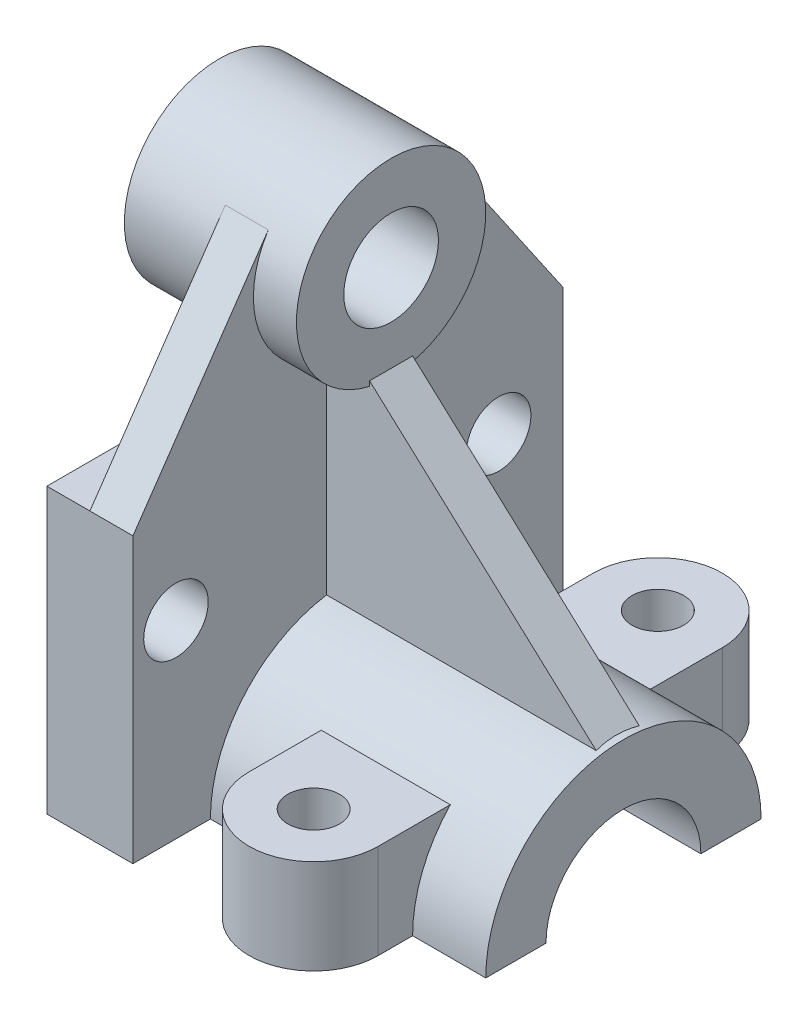
SolidWorks part; units mm, degrees
ref_plane "Front Plane" through (0, 0, 0) normal (0, 0, 1) x (1, 0, 0)
ref_plane "Top Plane" through (0, 0, 0) normal (0, 1, 0) x (1, 0, 0)
ref_plane "Right Plane" through (0, 0, 0) normal (1, 0, 0) x (0, 0, -1)
sketch "Sketch2" plane through (0, 0, 0) normal (0, 0, 1) x (1, 0, 0)
  line L0 (-22.1014, 0) -> (-22.1014, 66)
  line L1 (-22.1014, 66) -> (-2.1014, 66)
  line L2 (-2.1014, 66) -> (-2.1014, 0)
  line L3 (-2.1014, 0) -> (-22.1014, 0)
  dimension "D1" = 66
  dimension "D2" = 20
extrude "Boss-Extrude1" add sketch "Sketch2" against normal blind 100
sketch "Sketch3" plane through (-2.1014, 0, 0) normal (1, 0, 0) x (0, 0, -1)
  line L0 (0, 66) -> (100, 66)
  line L1 (0, 66) -> (32.2775, 113.0351)
  line L2 (67.7225, 113.0351) -> (100, 66)
  line L3 (100, 0) -> (0, 0) construction
  circle A0 centre (50, 100) radius 22
  circle A1 centre (50, 100) radius 11
  line M6 (100, 66) -> (0, 66)
  dimension "D1" = 44
  dimension "D2" = 22
  dimension "D3" = 100
extrude "Boss-Extrude2" add sketch "Sketch3" against normal blind 10 contours A0 L1 L2 M6 | L1 A0 L2 A1
sketch "Sketch4" plane through (-2.1014, 0, 0) normal (1, 0, 0) x (0, 0, -1)
  circle A1 centre (50, 100) radius 22
  circle A2 centre (50, 100) radius 11
extrude "Boss-Extrude3" add sketch "Sketch4" along normal blind 10
sketch "Sketch5" plane through (7.8986, 0, 0) normal (1, 0, 0) x (0, 0, -1)
  circle A0 centre (50, 100) radius 11
  circle A1 centre (50, 100) radius 22
extrude "Boss-Extrude4" add sketch "Sketch5" against normal blind 40
sketch "Sketch6" plane through (-2.1014, 0, 0) normal (1, 0, 0) x (0, 0, -1)
  line L0 (100, 0) -> (0, 0) construction
  line L1 (1.936, 0) -> (100, 0)
  circle A0 centre (50, 0) radius 32
  circle A1 centre (50, 0) radius 18
  dimension "D1" = 64
  dimension "D2" = 36
extrude "Boss-Extrude5" add sketch "Sketch6" along normal blind 64 contours A1 L1 A0
ref_plane "Plane1" through (0, 0, -50) normal (0, 0, -1) x (-1, 0, 0)
sketch "Sketch9" plane through (0, 0, -50) normal (0, 0, -1) x (-1, 0, 0)
  line L0 (-61.8986, 30.403) -> (4.3565, 30.403)
  line L1 (-61.8986, 30.403) -> (-7.8986, 79.7071)
  line L2 (-7.8986, 122) -> (-7.8986, 78) construction
  line L3 (-61.8986, 32) -> (-61.8986, 0) construction
  line L8 (-7.8986, 79.7071) -> (4.3565, 79.7071)
  line L9 (4.3565, 79.7071) -> (4.3565, 30.403)
extrude "Boss-Extrude10" add sketch "Sketch9" along normal mid plane 10
ref_plane "Plane2" through (29.8986, 0, 0) normal (1, 0, 0) x (0, 0, -1)
sketch "Sketch16" plane through (0, 0, 0) normal (0, -1, 0) x (1, 0, 0)
  line L0 (14.8986, -32) -> (14.8986, -10)
  line L1 (61.8986, -32) -> (-2.1014, -32) construction
  line L2 (44.8986, -32) -> (44.8986, -10)
  line L3 (14.8986, -68) -> (14.8986, -90)
  line L4 (61.8986, -68) -> (-2.1014, -68) construction
  line L5 (44.8986, -68) -> (44.8986, -90)
  line L6 (14.8986, -32) -> (44.8986, -32)
  line L7 (14.8986, -68) -> (44.8986, -68)
  line L8 (-2.1014, -100) -> (-2.1014, -82) construction
  arc A0 (14.8986, -10) -> (44.8986, -10) centre (29.8986, -10) cw
  arc A1 (14.8986, -90) -> (44.8986, -90) centre (29.8986, -90) ccw
  circle A2 centre (29.8986, -90) radius 6
  circle A3 centre (29.8986, -10) radius 6
  dimension "D1" = 15
  dimension "D3" = 12
  dimension "D4" = 12
  dimension "D2" = 32
  dimension "D5" = 80
extrude "Boss-Extrude11" add sketch "Sketch16" against normal blind 22
sketch "Sketch18" plane through (-2.1014, 0, 0) normal (1, 0, 0) x (0, 0, -1)
  line L0 (18, 0) -> (32, 0) construction
  line L1 (45, 79.7071) -> (45, 31.607) construction
  line L2 (100, 0) -> (100, 66) construction
  line L3 (100, 0) -> (82, 0) construction
  circle A0 centre (10, 44) radius 7.5
  circle A1 centre (85, 44) radius 7.5
  point P10 (0, 0)
  dimension "D3" = 15
  dimension "D4" = 15
  dimension "D1" = 44
  dimension "D2" = 35
  dimension "D5" = 15
  dimension "D6" = 44
extrude "Cut-Extrude2" cut sketch "Sketch18" against normal blind 22
sketch "Sketch10" plane through (0, 0, -45) normal (0, 0, 1) x (1, 0, 0)
  line L0 (7.8986, 91.348) -> (7.8986, 92.9821)
  line L1 (7.8986, 92.9821) -> (9.3087, 91.348)
  line L2 (7.8986, 92.9821) -> (60.8597, 31.607) construction
  line L3 (9.3087, 91.348) -> (7.8986, 91.348)
